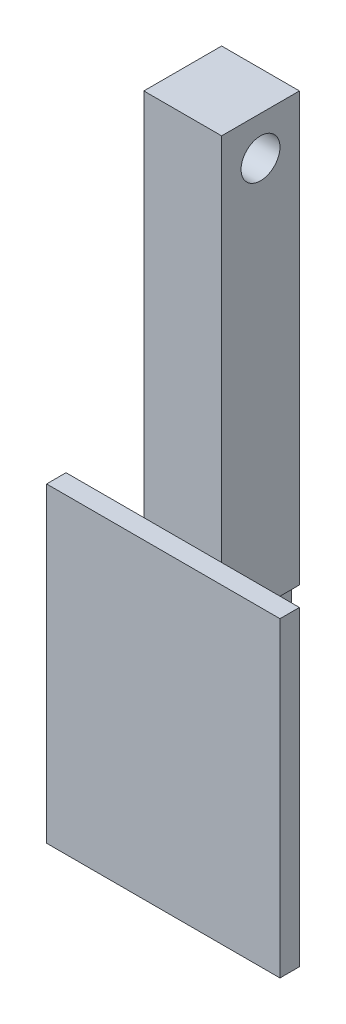
SolidWorks part; units mm, degrees
material "6061 Alloy"
ref_plane "Front Plane" through (0, 0, 0) normal (0, 0, 1) x (1, 0, 0)
ref_plane "Top Plane" through (0, 0, 0) normal (0, 1, 0) x (1, 0, 0)
ref_plane "Right Plane" through (0, 0, 0) normal (1, 0, 0) x (0, 0, -1)
sketch "Sketch1" plane through (0, 0, 0) normal (0, 1, 0) x (1, 0, 0)
  line L1 (-12.7, 12.7) -> (12.7, 12.7)
  line L2 (-12.7, 12.7) -> (-12.7, -12.7)
  line L3 (-12.7, -12.7) -> (12.7, -12.7)
  line L4 (12.7, 12.7) -> (12.7, -12.7)
  line L5 (-12.7, 12.7) -> (12.7, -12.7) construction
  line L6 (-12.7, -12.7) -> (12.7, 12.7) construction
  point P0 (0, 0)
  dimension "D1" = 25.4
  dimension "D2" = 25.4
extrude "Boss-Extrude1" add sketch "Sketch1" along normal blind 222.25
sketch "Sketch2" plane through (0, 0, 12.7) normal (0, 0, 1) x (1, 0, 0)
  line L0 (-12.7, 82.55) -> (-10.16, 82.55)
  line L1 (-12.7, 222.25) -> (-12.7, 0) construction
  line L2 (-10.16, 82.55) -> (-10.16, 0)
  line L3 (-12.7, 0) -> (12.7, 0) construction
  line L4 (-12.7, 82.55) -> (-12.7, 0)
  line L5 (-12.7, 0) -> (-10.16, 0)
  line L6 (0, 222.25) -> (0, -8.8405) construction
  line L7 (-12.7, 222.25) -> (12.7, 222.25) construction
  line L8 (12.7, 0) -> (10.16, 0)
  line L9 (12.7, 82.55) -> (12.7, 0)
  line L10 (10.16, 82.55) -> (10.16, 0)
  line L11 (12.7, 82.55) -> (10.16, 82.55)
  dimension "D1" = 2.54
  dimension "D2" = 82.55
extrude "Cut-Extrude1" cut sketch "Sketch2" against normal blind 222.25
sketch "Sketch3" plane through (12.7, 0, 0) normal (1, 0, 0) x (0, 0, -1)
  line L0 (0, 229.6875) -> (0, -13.7531) construction
  line L1 (-12.7, 222.25) -> (12.7, 222.25) construction
  line L2 (12.7, 82.55) -> (12.7, 0) construction
  line L3 (12.7, 0) -> (-12.7, 0) construction
  circle A0 centre (0, 209.55) radius 6.35
  circle A1 centre (6.35, 69.85) radius 3.175
  circle A2 centre (6.35, 29.21) radius 3.175
  dimension "D2" = 12.7
  dimension "D3" = 6.35
  dimension "D1" = 12.7
  dimension "D4" = 6.35
  dimension "D5" = 29.21
  dimension "D6" = 40.64
extrude "Cut-Extrude2" cut sketch "Sketch3" against normal blind 222.25
sketch "Sketch4" plane through (0, 0, 12.7) normal (0, 0, 1) x (1, 0, 0)
  line L0 (-12.7, 222.25) -> (12.7, 222.25) construction
  line L1 (-38.1, 101.6) -> (38.1, 101.6)
  line L2 (-38.1, 101.6) -> (-38.1, 0)
  line L3 (-38.1, 0) -> (38.1, 0)
  line L4 (38.1, 0) -> (38.1, 101.6)
  point P0 (0, 222.25)
  point P5 (0, 0)
  dimension "D1" = 76.2
  dimension "D2" = 101.6
extrude "Boss-Extrude3" add sketch "Sketch4" along normal blind 6.35
